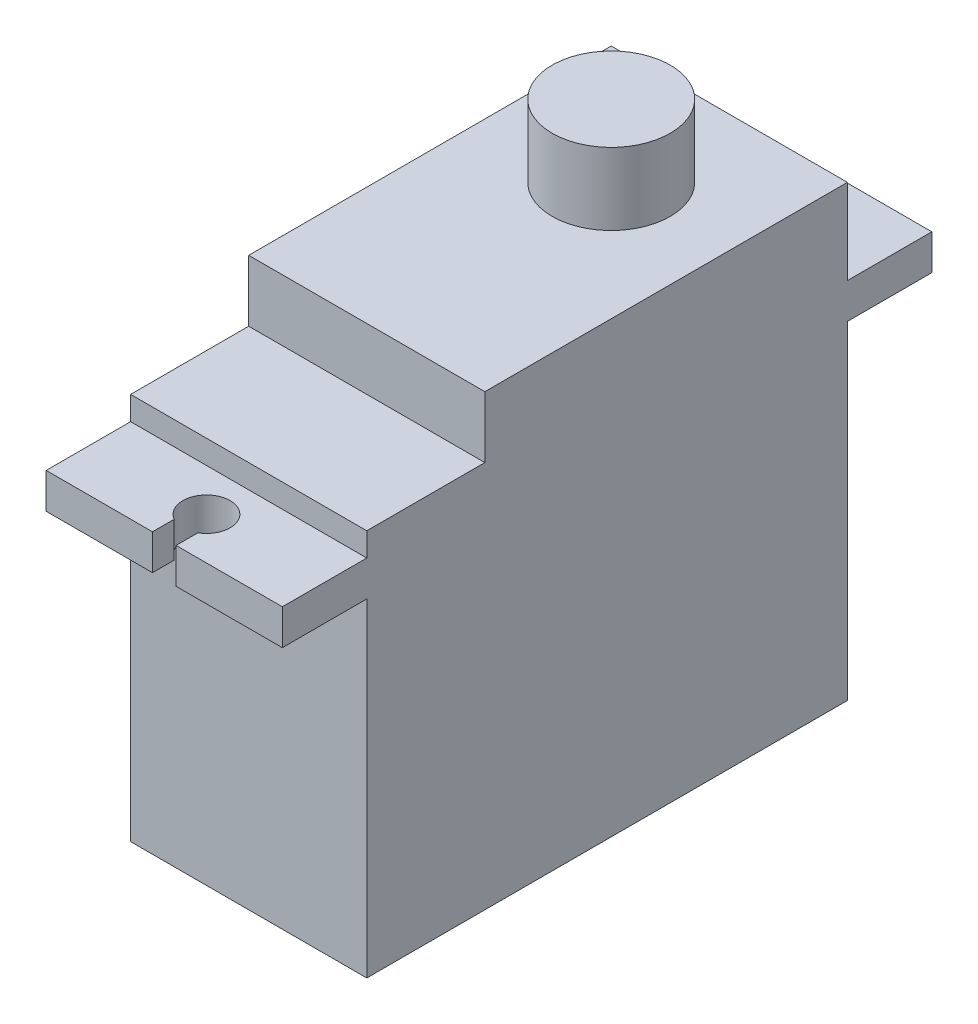
SolidWorks part; units mm, degrees
ref_plane "Front Plane" through (0, 0, 0) normal (0, 0, 1) x (1, 0, 0)
ref_plane "Top Plane" through (0, 0, 0) normal (0, 1, 0) x (1, 0, 0)
ref_plane "Right Plane" through (0, 0, 0) normal (1, 0, 0) x (0, 0, -1)
sketch "Sketch2" plane through (0, 0, 0) normal (1, 0, 0) x (0, 0, -1)
  line L1 (20.35, 16.4) -> (-20.35, 16.4)
  line L2 (20.35, 16.4) -> (20.35, -16.4)
  line L3 (20.35, -16.4) -> (-20.35, -16.4)
  line L4 (-20.35, 16.4) -> (-20.35, -16.4)
  line L5 (20.35, 16.4) -> (-20.35, -16.4) construction
  line L6 (20.35, -16.4) -> (-20.35, 16.4) construction
  line L7 (-20.35, 11.4) -> (-27.5, 11.4)
  line L8 (-20.35, 11.4) -> (-20.35, 14.4)
  line L9 (-20.35, 14.4) -> (-27.5, 14.4)
  line L10 (-27.5, 11.4) -> (-27.5, 14.4)
  line L11 (20.35, 14.4) -> (27.5, 14.4)
  line L12 (20.35, 14.4) -> (20.35, 11.4)
  line L13 (20.35, 11.4) -> (27.5, 11.4)
  line L14 (27.5, 14.4) -> (27.5, 11.4)
  line L15 (-10.35, 16.4) -> (20.35, 16.4)
  line L16 (-10.35, 16.4) -> (-10.35, 21.6)
  line L17 (-10.35, 21.6) -> (20.35, 21.6)
  line L18 (20.35, 16.4) -> (20.35, 21.6)
  line L19 (5.35, 21.6) -> (15.35, 21.6)
  line L20 (5.35, 21.6) -> (5.35, 27.7)
  line L21 (5.35, 27.7) -> (15.35, 27.7)
  line L22 (15.35, 21.6) -> (15.35, 27.7)
  point P0 (0, 0)
  point P17 (-41.1225, 12.7473)
  point P22 (67.5828, 4.9973)
  point P23 (68.7157, 10.9452)
  point P24 (-67.2765, 18.7282)
  point P25 (0, 0)
  point P26 (61.6639, 21.3684)
  point P27 (93.8907, 14.3392)
  point P28 (1.0949, 14.3392)
  point P29 (21.3532, 15.2541)
  point P30 (-41.2926, 14.4623)
  point P31 (5.7192, 28.5205)
  point P32 (10.35, 27.7)
  point P34 (-6.9301, 15.4883)
  point P35 (0, 0)
  point P36 (0, 0)
  point P37 (10, 22.9334)
  point P39 (15.8204, 21.6)
  dimension "D1" = 38
  dimension "D2" = 27.8
  dimension "D3" = 40.7
  dimension "D4" = 55
  dimension "D5" = 44.1
  dimension "D6" = 10
  dimension "D7" = 2
  dimension "D8" = 3
  dimension "D9" = 10
  dimension "D10" = 10
extrude "Boss-Extrude1" add sketch "Sketch2" along normal mid plane 20 contours L1 L4 L3 L2 | L10 L7 L4 L9 | L14 L11 L2 L13 | L1 L18 L17 L16
sketch "Sketch3" plane through (0, 21.6, 0) normal (0, 1, 0) x (1, 0, 0)
  line L1 (10, -10.35) -> (-10, -10.35) construction
  line L2 (10, 20.35) -> (-10, 20.35) construction
  circle A0 centre (0, 10.35) radius 5
  point P2 (0, 0)
  point P6 (0, 0)
  point P9 (0, -10.35)
  point P10 (0, 0)
  point P11 (0, 0)
  dimension "D1" = 10
  dimension "D2" = 10
extrude "Boss-Extrude2" add sketch "Sketch3" along normal blind 6.1
sketch "Sketch4" plane through (0, 14.4, 0) normal (0, 1, 0) x (1, 0, 0)
  line L0 (0, -23.925) -> (0, 23.925) construction
  line L1 (-10, -27.5) -> (-10, 27.5) construction
  line L2 (10, -20.35) -> (10, -27.5) construction
  line L3 (10, -27.5) -> (-10, -27.5) construction
  line L4 (-1, -27.5) -> (1, -27.5)
  line L5 (-1, -27.5) -> (-1, -25.6571)
  line L6 (-1, -25.6571) -> (1, -25.6571)
  line L7 (1, -27.5) -> (1, -25.6571)
  line L8 (10, 27.5) -> (-10, 27.5) construction
  line L9 (1, 27.5) -> (-1, 27.5)
  line L10 (1, 27.5) -> (1, 25.6571)
  line L11 (1, 25.6571) -> (-1, 25.6571)
  line L12 (-1, 27.5) -> (-1, 25.6571)
  circle A0 centre (0, -23.925) radius 2
  circle A1 centre (0, 23.925) radius 2
  point P4 (-10, 0)
  point P8 (0, 0)
  point P14 (10, -23.925)
  point P26 (0, 0)
  point P27 (1.3285, 25.4201)
  line M9 (-10, -27.5) -> (10, -27.5)
  dimension "D1" = 4
  dimension "D2" = 2
extrude "Cut-Extrude1" cut sketch "Sketch4" against normal through all contours A0 L5 L7 M9 | L6 A0 | L6 A0 | L11 A1 | L11 A1 | A1 L10 L9 L12
